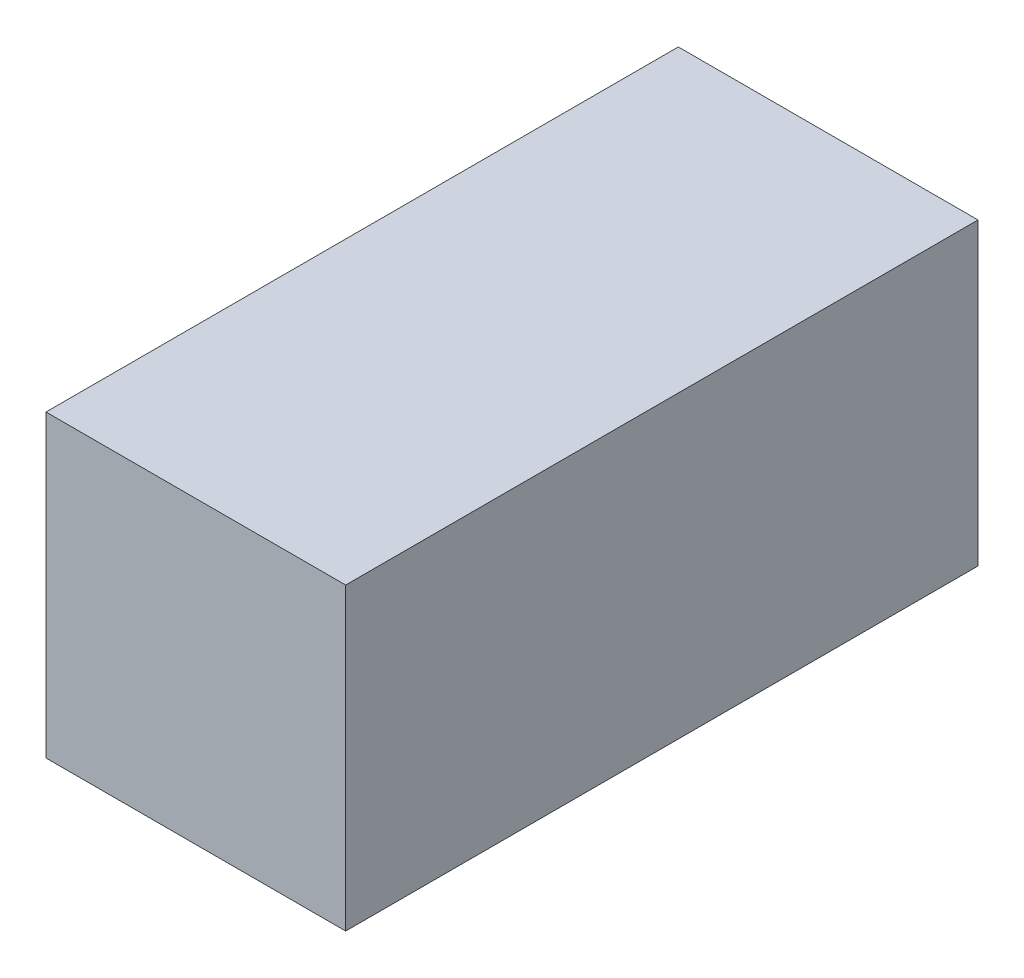
SolidWorks part; units mm, degrees
ref_plane "Front Plane" through (0, 0, 0) normal (0, 0, 1) x (1, 0, 0)
ref_plane "Top Plane" through (0, 0, 0) normal (0, 1, 0) x (1, 0, 0)
ref_plane "Right Plane" through (0, 0, 0) normal (1, 0, 0) x (0, 0, -1)
sketch "Sketch1" plane through (0, 0, 0) normal (0, 0, 1) x (1, 0, 0)
  line L1 (-38.722, 31.4867) -> (-13.322, 31.4867)
  line L2 (-38.722, 31.4867) -> (-38.722, 6.0867)
  line L3 (-38.722, 6.0867) -> (-13.322, 6.0867)
  line L4 (-13.322, 31.4867) -> (-13.322, 6.0867)
  point P4 (-43.7236, 18.1509)
  point P5 (-35.4952, 18.1509)
  point P6 (-38.722, 18.7963)
  dimension "D1" = 25.4
  dimension "D2" = 25.4
extrude "Boss-Extrude1" add sketch "Sketch1" along normal blind 53.594 contours L1 L4 L3 L2
